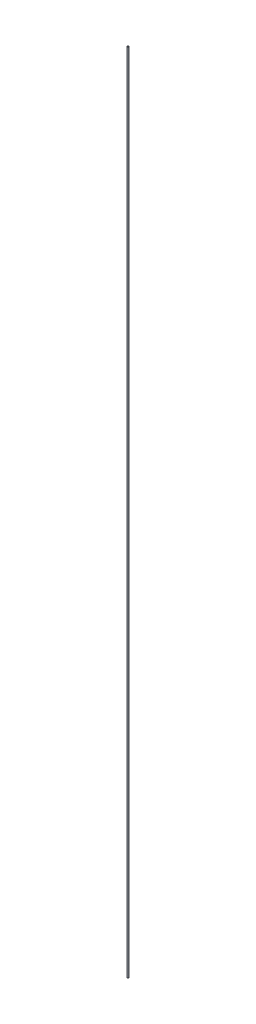
SolidWorks part; units mm, degrees
ref_plane "Front Plane" through (0, 0, 0) normal (0, 0, 1) x (1, 0, 0)
ref_plane "Top Plane" through (0, 0, 0) normal (0, 1, 0) x (1, 0, 0)
ref_plane "Right Plane" through (0, 0, 0) normal (1, 0, 0) x (0, 0, -1)
sketch "Sketch1" plane through (0, 0, 0) normal (0, 0, 1) x (1, 0, 0)
  line L0 (0, 0) -> (0, 8215.884)
  dimension "Length from Tank Model" = 8215.884
sweep "Sweep1" add path "Sketch1" circular profile diameter 12.7 parameters "D3"=12.7
equation "\"rebar diameter\"= .5"
equation "\"D3@Sweep1\"=\"rebar diameter\""
